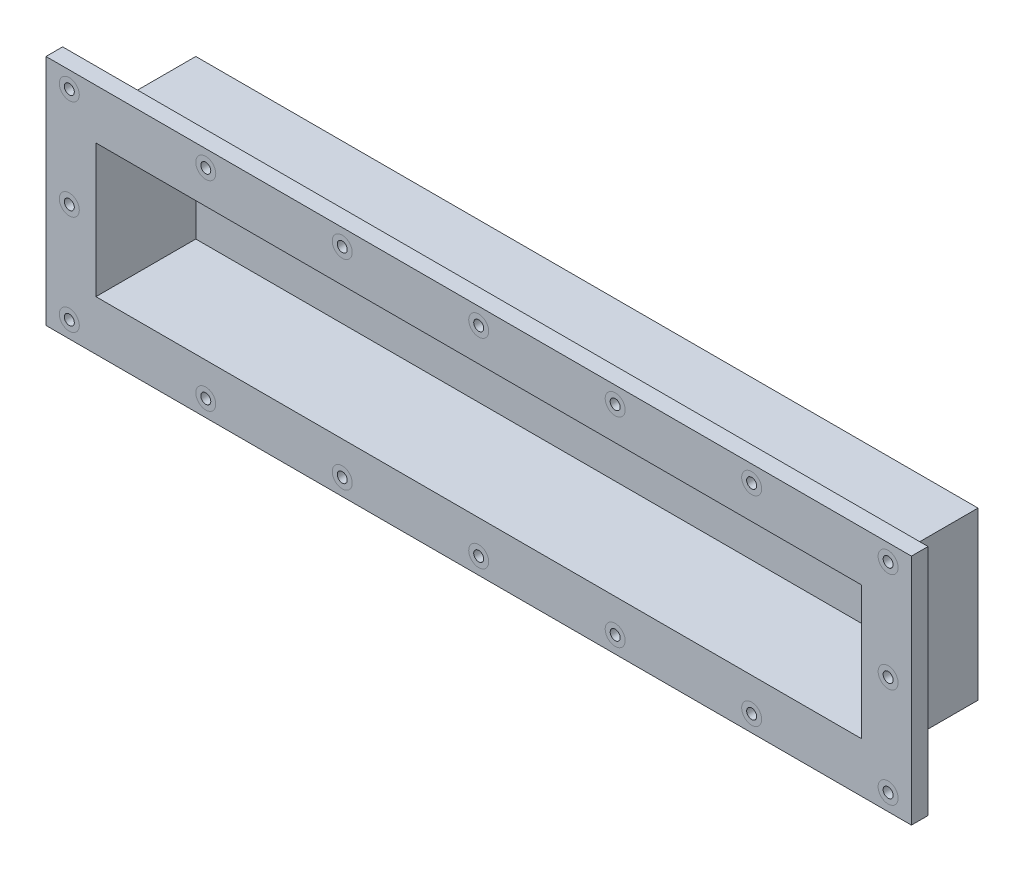
SolidWorks part; units mm, degrees
ref_plane "前视基准面" through (0, 0, 0) normal (0, 0, 1) x (1, 0, 0)
ref_plane "上视基准面" through (0, 0, 0) normal (0, 1, 0) x (1, 0, 0)
ref_plane "右视基准面" through (0, 0, 0) normal (1, 0, 0) x (0, 0, -1)
sketch "草图1" plane through (0, 0, 0) normal (0, 0, 1) x (1, 0, 0)
  line L1 (-235, 50) -> (235, 50)
  line L2 (-235, 50) -> (-235, -50)
  line L3 (-235, -50) -> (235, -50)
  line L4 (235, 50) -> (235, -50)
  line L5 (0, -50) -> (0, 50) construction
  line L6 (-235, 0) -> (235, 0) construction
  point P0 (0, 0)
  dimension "D1" = 100
  dimension "D2" = 470
extrude "凸台-拉伸1" add sketch "草图1" along normal blind 50
sketch "草图2" plane through (0, 0, 50) normal (0, 0, 1) x (1, 0, 0)
  line L1 (-230, 40) -> (230, 40)
  line L2 (-230, 40) -> (-230, -40)
  line L3 (-230, -40) -> (230, -40)
  line L4 (230, 40) -> (230, -40)
  line L5 (0, -40) -> (0, 40) construction
  line L6 (-230, 0) -> (230, 0) construction
  point P0 (0, 0)
  dimension "D1" = 460
  dimension "1503" = 80
extrude "切除-拉伸1" cut sketch "草图2" against normal blind 180
sketch "草图3" plane through (0, 0, 50) normal (0, 0, 1) x (1, 0, 0)
  line L1 (-260, 70) -> (260, 70)
  line L2 (-260, 70) -> (-260, -70)
  line L3 (-260, -70) -> (260, -70)
  line L4 (260, 70) -> (260, -70)
  line L5 (0, -70) -> (0, 70) construction
  line L6 (-260, 0) -> (260, 0) construction
  line L7 (-230, 40) -> (230, 40)
  line L8 (-230, 40) -> (-230, -40)
  line L9 (-230, -40) -> (230, -40)
  line L10 (230, 40) -> (230, -40)
  line L11 (0, -40) -> (0, 40) construction
  line L12 (-230, 0) -> (230, 0) construction
  point P0 (0, 0)
  point P4 (0, 0)
  dimension "D1" = 520
  dimension "D2" = 140
extrude "凸台-拉伸2" add sketch "草图3" along normal blind 10
sketch "草图4" plane through (0, 0, 60) normal (0, 0, 1) x (1, 0, 0)
  line L0 (260, 70) -> (-260, 70) construction
  line L1 (0, 0) -> (57.5903, 0) construction
  line L2 (0, 0) -> (0, 50.2655) construction
  circle A0 centre (0, 60) radius 6
  circle A1 centre (-82, 60) radius 6
  circle A2 centre (-164, 60) radius 6
  circle A3 centre (-246, 60) radius 6
  circle A13 centre (246, 0) radius 6
  circle A14 centre (246, 60) radius 6
  circle A15 centre (164, 60) radius 6
  circle A16 centre (82, 60) radius 6
  circle A17 centre (-246, 0) radius 6
  circle A19 centre (82, -60) radius 6
  circle A20 centre (164, -60) radius 6
  circle A21 centre (246, -60) radius 6
  circle A22 centre (-246, -60) radius 6
  circle A23 centre (-164, -60) radius 6
  circle A24 centre (-82, -60) radius 6
  circle A25 centre (0, -60) radius 6
  circle A26 centre (-246, -60) radius 6 [skipped]
  dimension "D2" = 12
  dimension "D4" = 3
  dimension "D1" = 10
  dimension "D5" = 60
  dimension "D3" = 4
extrude "切除-拉伸2" cut sketch "草图4" against normal blind 10
sketch "草图5" plane through (0, 0, 60) normal (0, 0, 1) x (1, 0, 0)
  line L0 (0, 0) -> (43.5025, 0) construction
  line L1 (0, 0) -> (0, 45.0991) construction
  circle A0 centre (0, 60) radius 6
  circle A1 centre (0, 60) radius 3
  circle A2 centre (-82, 60) radius 6
  circle A3 centre (-82, 60) radius 3
  circle A4 centre (-164, 60) radius 6
  circle A5 centre (-164, 60) radius 3
  circle A6 centre (-246, 60) radius 6
  circle A7 centre (-246, 60) radius 3
  circle A10 centre (-246, -60) radius 3
  circle A11 centre (-246, -60) radius 6
  circle A12 centre (-164, -60) radius 3
  circle A13 centre (-164, -60) radius 6
  circle A14 centre (-82, -60) radius 3
  circle A15 centre (-82, -60) radius 6
  circle A16 centre (0, -60) radius 3
  circle A17 centre (0, -60) radius 6
  circle A18 centre (82, -60) radius 6
  circle A19 centre (82, -60) radius 3
  circle A20 centre (164, -60) radius 6
  circle A21 centre (164, -60) radius 3
  circle A22 centre (246, -60) radius 6
  circle A23 centre (246, -60) radius 3
  circle A24 centre (246, 0) radius 3
  circle A25 centre (246, 0) radius 6
  circle A26 centre (246, 60) radius 3
  circle A27 centre (246, 60) radius 6
  circle A28 centre (164, 60) radius 3
  circle A29 centre (164, 60) radius 6
  circle A30 centre (82, 60) radius 3
  circle A31 centre (82, 60) radius 6
  circle A32 centre (-246, 0) radius 6
  circle A33 centre (-246, 0) radius 3
  point P18 (0, 0)
  dimension "D1" = 6
  dimension "D3" = 6
  dimension "D4" = 60
  dimension "D5" = 60
  dimension "D2" = 4
extrude "凸台-拉伸3" add sketch "草图5" against normal blind 7 separate body
sketch "草图6" plane through (0, 0, 0) normal (0, 0, -1) x (-1, 0, 0)
  line L1 (-235, 50) -> (235, 50)
  line L2 (-235, 50) -> (-235, -50)
  line L3 (-235, -50) -> (235, -50)
  line L4 (235, 50) -> (235, -50)
extrude "凸台-拉伸4" add sketch "草图6" along normal blind 5
